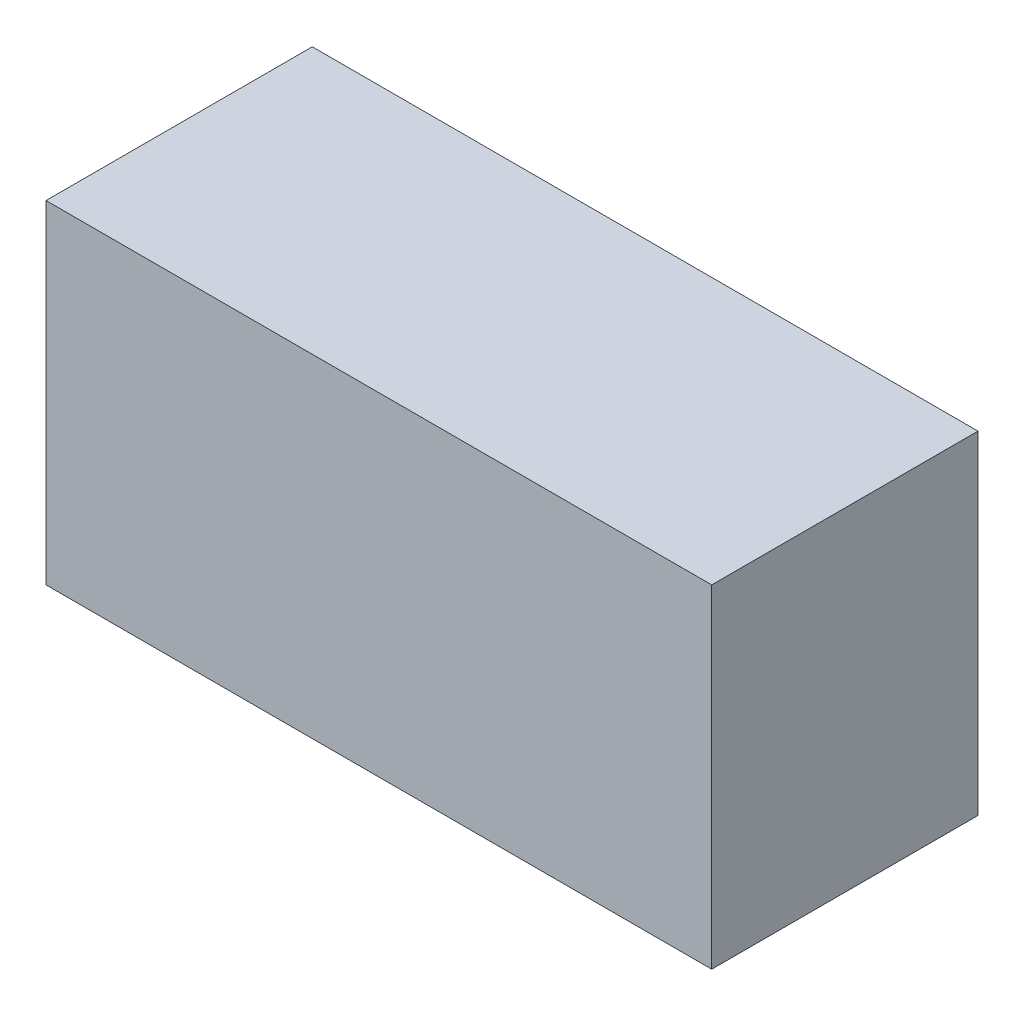
SolidWorks part; units mm, degrees
ref_plane "Front Plane" through (0, 0, 0) normal (0, 0, 1) x (1, 0, 0)
ref_plane "Top Plane" through (0, 0, 0) normal (0, 1, 0) x (1, 0, 0)
ref_plane "Right Plane" through (0, 0, 0) normal (1, 0, 0) x (0, 0, -1)
sketch "Sketch1" plane through (0, 0, 0) normal (0, 0, 1) x (1, 0, 0)
  line L1 (0, 0) -> (25.4, 0)
  line L2 (0, 0) -> (0, -12.7)
  line L3 (0, -12.7) -> (25.4, -12.7)
  line L4 (25.4, 0) -> (25.4, -12.7)
  dimension "D1" = 25.4
  dimension "D2" = 12.7
extrude "Boss-Extrude1" add sketch "Sketch1" along normal blind 10.16
sketch "Sketch2" plane through (0, 0, 0) normal (-1, 0, 0) x (0, 0, 1)
  line L0 (10.16, -6.35) -> (-0.6439, -6.35) construction
  line L1 (10.16, 0) -> (10.16, -12.7) construction
  line L2 (5.08, 0) -> (5.08, -15.0467) construction
  line L3 (10.16, 0) -> (0, 0) construction
  line L4 (7.4299, -4.9933) -> (7.4299, -7.7067)
  line L5 (7.4299, -7.7067) -> (5.08, -9.0635)
  line L6 (5.08, -9.0635) -> (2.7301, -7.7067)
  line L7 (2.7301, -7.7067) -> (2.7301, -4.9933)
  line L8 (2.7301, -4.9933) -> (5.08, -3.6365)
  line L9 (5.08, -3.6365) -> (7.4299, -4.9933)
  line L10 (5.08, -2.7567) -> (8.1919, -4.5533)
  line L11 (8.1919, -4.5533) -> (8.1919, -8.1467)
  line L12 (8.1919, -8.1467) -> (5.08, -9.9433)
  line L13 (5.08, -9.9433) -> (1.9681, -8.1467)
  line L14 (1.9681, -8.1467) -> (1.9681, -4.5533)
  line L15 (1.9681, -4.5533) -> (5.08, -2.7567)
  point P10 (7.1198, -9.2394)
  point P15 (7.6259, -5.8775)
  point P16 (7.4299, -6.35)
  point P17 (0, 0)
  dimension "D1" = 120
  dimension "D2" = 120
  dimension "D3" = 0.762
extrude "Boss-Extrude2" add sketch "Sketch2" along normal blind 1.27
